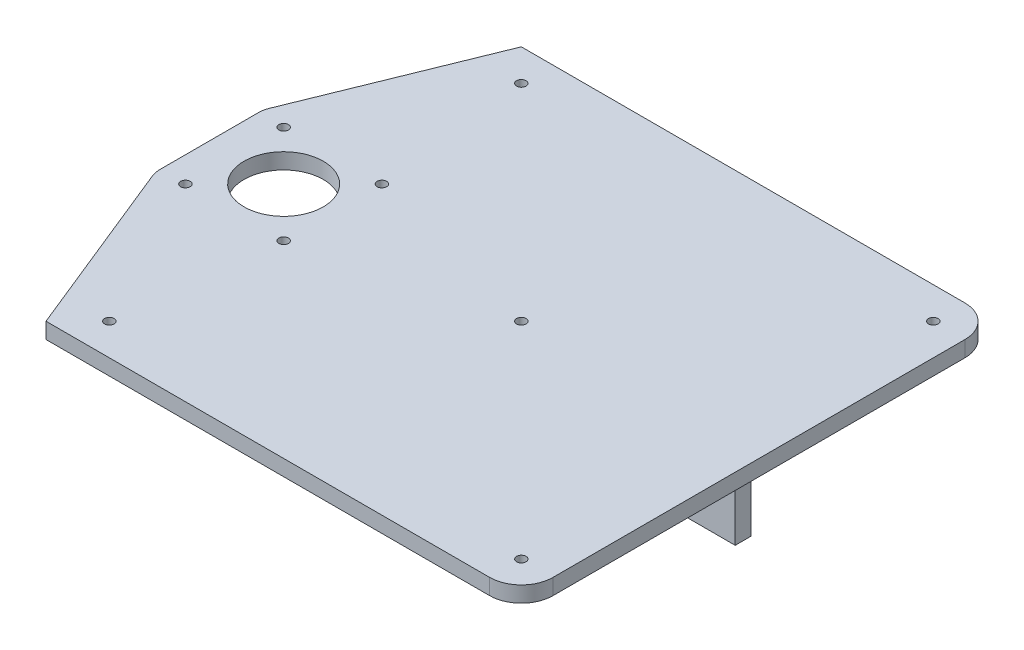
SolidWorks part; units mm, degrees
ref_plane "Front Plane" through (0, 0, 0) normal (0, 0, 1) x (1, 0, 0)
ref_plane "Top Plane" through (0, 0, 0) normal (0, 1, 0) x (1, 0, 0)
ref_plane "Right Plane" through (0, 0, 0) normal (1, 0, 0) x (0, 0, -1)
sketch "Sketch1" plane through (0, 0, 0) normal (0, 1, 0) x (1, 0, 0)
  line L1 (-75, -75) -> (65, -75)
  line L3 (-75, 75) -> (65, 75)
  line L4 (75, -65) -> (75, 65)
  line L5 (-75, -75) -> (75, 75) construction
  line L6 (-75, 75) -> (75, -75) construction
  line L11 (-90.5, -15.5) -> (-59.5, 15.5) construction
  line L12 (-90.5, 15.5) -> (-59.5, -15.5) construction
  line L16 (-97.9134, -18.5069) -> (-75, -75)
  line L17 (-98.5, -15.5) -> (-98.5, 15.5)
  line L18 (-98.5, 0) -> (-75, 0) construction
  line L19 (-97.9134, 18.5069) -> (-75, 75)
  circle A0 centre (-90.5, 15.5) radius 1.5
  circle A1 centre (-90.5, -15.5) radius 1.5
  circle A2 centre (-59.5, -15.5) radius 1.5
  circle A3 centre (-59.5, 15.5) radius 1.5
  circle A4 centre (-75, 0) radius 12.5
  arc A5 (-98.5, -15.5) -> (-97.9134, -18.5069) centre (-90.5, -15.5) ccw
  arc A6 (-98.5, 15.5) -> (-97.9134, 18.5069) centre (-90.5, 15.5) cw
  arc A7 (65, -75) -> (75, -65) centre (65, -65) ccw
  arc A8 (65, 75) -> (75, 65) centre (65, 65) cw
  circle A9 centre (-65, 65) radius 1.5
  circle A10 centre (65, 65) radius 1.5
  circle A11 centre (65, -65) radius 1.5
  circle A12 centre (-65, -65) radius 1.5
  circle A13 centre (0, 0) radius 1.5
  point P0 (0, 0)
  point P6 (-75, 0)
  dimension "D3" = 3
  dimension "D2" = 25
  dimension "D6" = 10
  dimension "D7" = 3
  dimension "D8" = 3
  dimension "D1" = 150
  dimension "D4" = 31
  dimension "D5" = 8
extrude "Boss-Extrude1" add sketch "Sketch1" along normal blind 5
sketch "Sketch2" plane through (0, 5, 0) normal (0, 1, 0) x (1, 0, 0)
  line L1 (70, 2.5) -> (50, 2.5)
  line L2 (70, 2.5) -> (70, -2.5)
  line L3 (70, -2.5) -> (50, -2.5)
  line L4 (50, 2.5) -> (50, -2.5)
  line L5 (75, -65) -> (75, 65) construction
  line L9 (-75, -75) -> (65, -75) construction
  dimension "D1" = 20
  dimension "D2" = 5
  dimension "D3" = 5
  dimension "D4" = 72.5
extrude "Boss-Extrude2" add sketch "Sketch2" against normal blind 25
